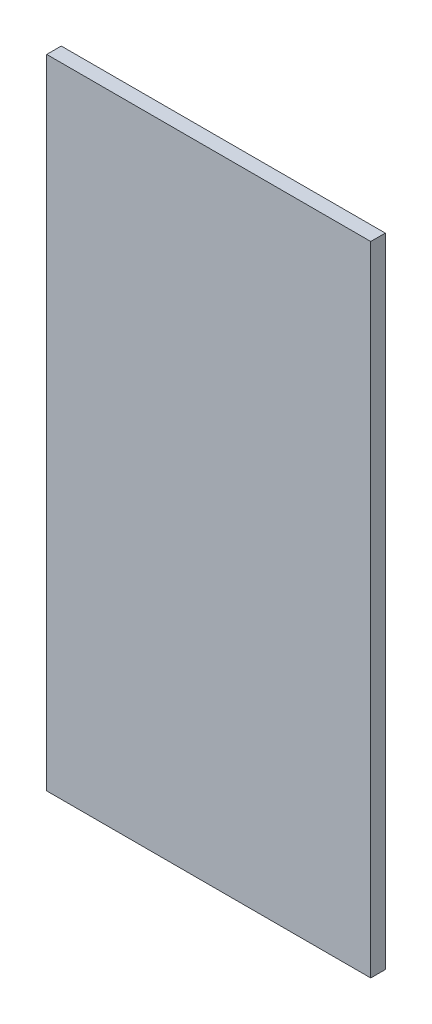
SolidWorks part; units mm, degrees
ref_plane "前视基准面" through (0, 0, 0) normal (0, 0, 1) x (1, 0, 0)
ref_plane "上视基准面" through (0, 0, 0) normal (0, 1, 0) x (1, 0, 0)
ref_plane "右视基准面" through (0, 0, 0) normal (1, 0, 0) x (0, 0, -1)
other "Configuration Table"
sketch "草图1" plane through (0, 0, 0) normal (0, 0, 1) x (1, 0, 0)
  line L1 (33.4149, -65.7746) -> (-33.4149, -65.7746)
  line L2 (33.4149, -65.7746) -> (33.4149, 65.7746)
  line L3 (33.4149, 65.7746) -> (-33.4149, 65.7746)
  line L4 (-33.4149, -65.7746) -> (-33.4149, 65.7746)
  line L5 (33.4149, -65.7746) -> (-33.4149, 65.7746) construction
  line L6 (33.4149, 65.7746) -> (-33.4149, -65.7746) construction
  point P0 (0, 0)
extrude "凸台-拉伸1" add sketch "草图1" along normal blind 3
